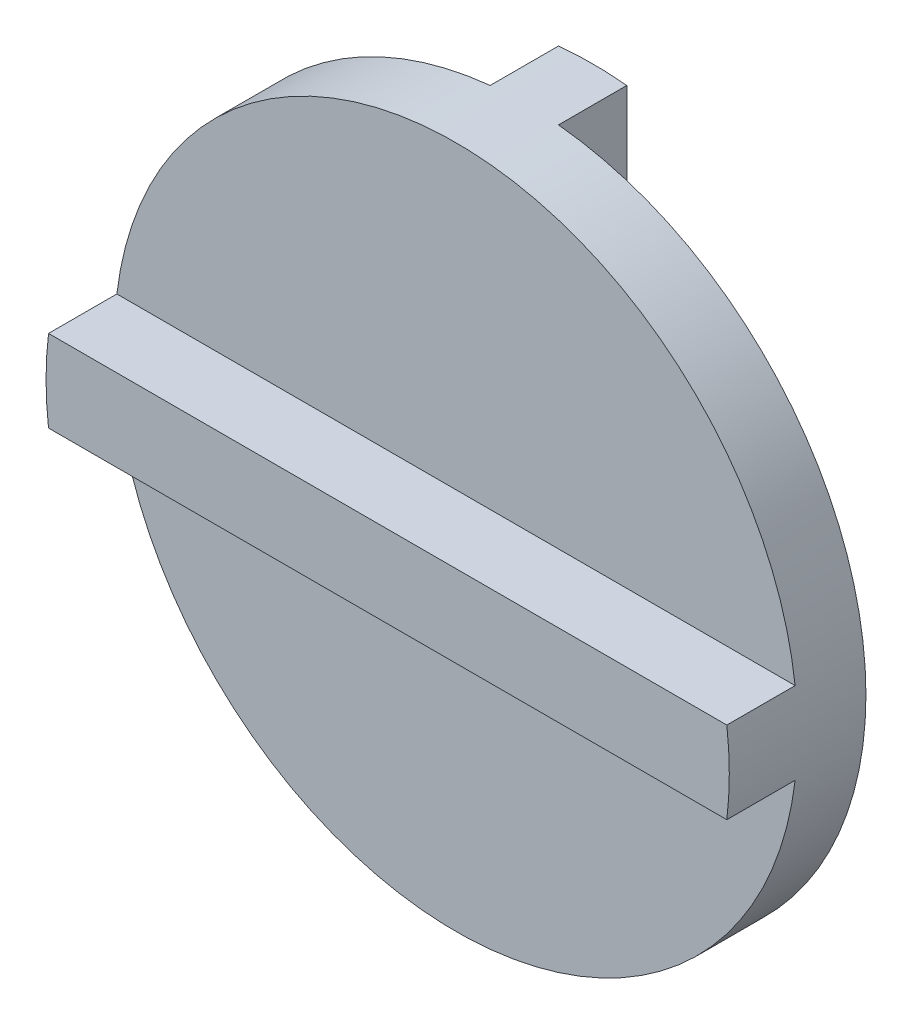
SolidWorks part; units mm, degrees
ref_plane "Front Plane" through (0, 0, 0) normal (0, 0, 1) x (1, 0, 0)
ref_plane "Top Plane" through (0, 0, 0) normal (0, 1, 0) x (1, 0, 0)
ref_plane "Right Plane" through (0, 0, 0) normal (1, 0, 0) x (0, 0, -1)
sketch "Sketch1" plane through (0, 0, 0) normal (0, 0, 1) x (1, 0, 0)
  circle A0 centre (0, 0) radius 50
  dimension "D1" = 100
extrude "Boss-Extrude1" add sketch "Sketch1" along normal blind 10
sketch "Sketch2" plane through (0, 0, 10) normal (0, 0, 1) x (1, 0, 0)
  line L0 (-49.6387, 6) -> (49.6387, 6)
  line L1 (-49.6387, -6) -> (49.6387, -6)
  circle A0 centre (0, 0) radius 50 construction
  arc A1 (-49.6387, 6) -> (-49.6387, -6) centre (0, 0) ccw
  arc A2 (49.6387, -6) -> (49.6387, 6) centre (0, 0) ccw
  dimension "D1" = 12
extrude "Boss-Extrude2" add sketch "Sketch2" along normal blind 10 contours L0 A2 L1 A1
sketch "Sketch3" plane through (0, 0, 0) normal (0, 0, -1) x (-1, 0, 0)
  line L0 (-5, 49.7494) -> (-5, -49.7494)
  line L1 (5, 49.7494) -> (5, -49.7494)
  circle A0 centre (0, 0) radius 50 construction
  arc A1 (-5, -49.7494) -> (5, -49.7494) centre (0, 0) ccw
  arc A2 (5, 49.7494) -> (-5, 49.7494) centre (0, 0) ccw
  dimension "D1" = 10
extrude "Boss-Extrude3" add sketch "Sketch3" along normal blind 10
